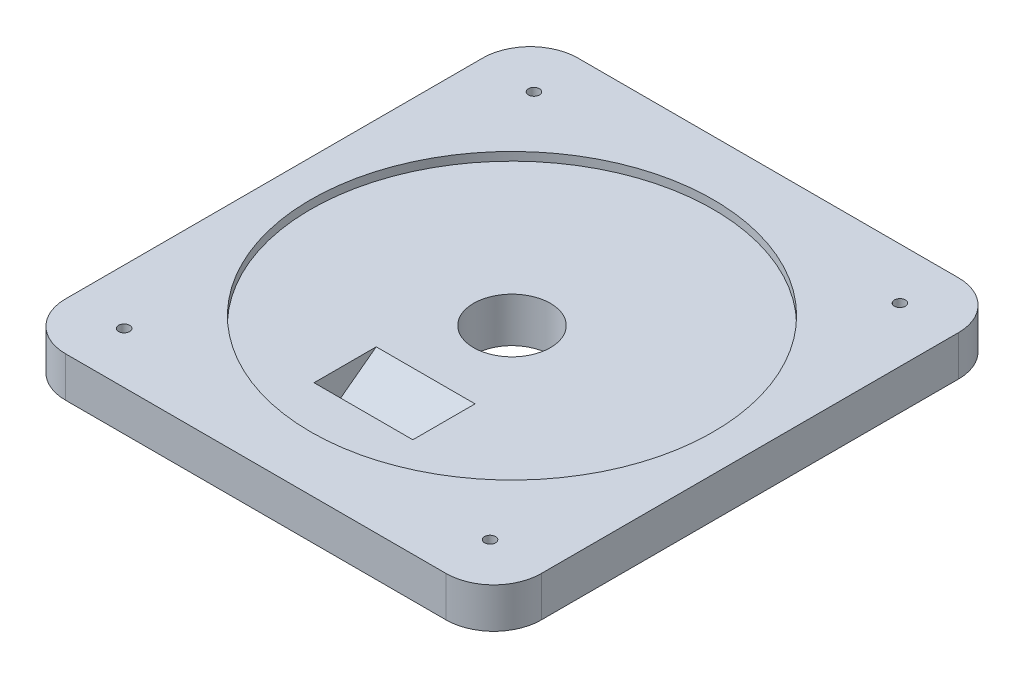
SolidWorks part; units mm, degrees
material "1060 Alloy"
ref_plane "Front Plane" through (0, 0, 0) normal (0, 0, 1) x (1, 0, 0)
ref_plane "Top Plane" through (0, 0, 0) normal (0, 1, 0) x (1, 0, 0)
ref_plane "Right Plane" through (0, 0, 0) normal (1, 0, 0) x (0, 0, -1)
sketch "Sketch2" plane through (0, 0, 0) normal (0, 1, 0) x (1, 0, 0)
  line L1 (-82.55, -88.9) -> (82.55, -88.9)
  line L2 (-82.55, -88.9) -> (-82.55, 88.9)
  line L3 (-82.55, 88.9) -> (82.55, 88.9)
  line L4 (82.55, -88.9) -> (82.55, 88.9)
  point P0 (0, 0)
  point P6 (82.55, 0)
  point P7 (0, 88.9)
  dimension "D1" = 165.1
  dimension "D2" = 177.8
extrude "Boss-Extrude1" add sketch "Sketch2" along normal blind 13.97
fillet "Fillet1" radius 16.51 4 edges at (82.55, 6.985, -88.9) (-82.55, 6.985, -88.9) (-82.55, 6.985, 88.9) (82.55, 6.985, 88.9)
sketch "Sketch3" plane through (0, 0, 0) normal (0, -1, 0) x (1, 0, 0)
  line L0 (-82.55, -72.39) -> (-82.55, 72.39) construction
  line L1 (-66.04, 88.9) -> (66.04, 88.9) construction
  line L2 (66.04, -88.9) -> (-66.04, -88.9) construction
  line L3 (82.55, 72.39) -> (82.55, -72.39) construction
  circle A0 centre (-63.5, 71.12) radius 1.905
  circle A1 centre (63.5, 71.12) radius 1.905
  circle A2 centre (-63.5, -71.12) radius 1.905
  circle A3 centre (63.5, -71.12) radius 1.905
  dimension "D5" = 3.81
  dimension "D1" = 19.05
  dimension "D2" = 17.78
  dimension "D3" = 17.78
  dimension "D4" = 19.05
extrude "Cut-Extrude1" cut sketch "Sketch3" against normal through all
sketch "Sketch5" plane through (0, 0, 0) normal (0, -1, 0) x (1, 0, 0)
  line L0 (-49.2524, 49.53) -> (49.2524, 49.53)
  arc A0 (-49.2524, 49.53) -> (49.2524, 49.53) centre (0, 0) ccw
  dimension "D1" = 139.7
  dimension "D2" = 49.53
extrude "Boss-Extrude2" add sketch "Sketch5" along normal blind 4.445
sketch "Sketch4" plane through (0, 0, 0) normal (0, -1, 0) x (1, 0, 0)
  circle A1 centre (0, 0) radius 13.335
  dimension "D2" = 26.67
extrude "Cut-Extrude3" cut sketch "Sketch4" against normal through all both and the other way through all contours A1
sketch "Sketch7" plane through (0, 0, 0) normal (0, -1, 0) x (1, 0, 0)
  line L0 (-17.145, 51.562) -> (17.145, 51.562)
  line L2 (-66.04, 88.9) -> (66.04, 88.9) construction
  line L6 (82.55, -72.39) -> (82.55, 72.39)
  line L7 (-66.04, -88.9) -> (66.04, -88.9)
  line L8 (-82.55, 72.39) -> (-82.55, -72.39)
  line L9 (66.04, 88.9) -> (-66.04, 88.9)
  line L10 (82.55, -72.39) -> (82.55, 72.39)
  line L11 (-66.04, -88.9) -> (66.04, -88.9)
  line L12 (-82.55, 72.39) -> (-82.55, -72.39)
  line L13 (66.04, 88.9) -> (-66.04, 88.9)
  arc A4 (66.04, -88.9) -> (82.55, -72.39) centre (66.04, -72.39) ccw
  arc A5 (-82.55, -72.39) -> (-66.04, -88.9) centre (-66.04, -72.39) ccw
  arc A6 (-66.04, 88.9) -> (-82.55, 72.39) centre (-66.04, 72.39) ccw
  arc A7 (82.55, 72.39) -> (66.04, 88.9) centre (66.04, 72.39) ccw
  arc A8 (66.04, -88.9) -> (82.55, -72.39) centre (66.04, -72.39) ccw
  arc A9 (-82.55, -72.39) -> (-66.04, -88.9) centre (-66.04, -72.39) ccw
  arc A10 (-66.04, 88.9) -> (-82.55, 72.39) centre (-66.04, 72.39) ccw
  arc A11 (82.55, 72.39) -> (66.04, 88.9) centre (66.04, 72.39) ccw
  point P2 (0, 51.562)
  dimension "D1" = 37.338
  dimension "D2" = 34.29
  dimension "D3" = 0
sketch "Sketch9" plane through (0, 13.97, 0) normal (0, 1, 0) x (1, 0, 0)
  circle A0 centre (0, 0) radius 69.85
  dimension "D1" = 139.7
extrude "Cut-Extrude4" cut sketch "Sketch9" against normal blind 2.921
sketch "Sketch12" plane through (0, 11.049, 0) normal (0, 1, 0) x (1, 0, 0)
  line L0 (17.145, -51.562) -> (-17.145, -51.562)
  line L1 (-66.04, -88.9) -> (66.04, -88.9) construction
  line L2 (17.145, -51.562) -> (17.145, -29.972)
  line L3 (17.145, -29.972) -> (-17.145, -29.972)
  line L4 (-17.145, -29.972) -> (-17.145, -51.562)
  point P2 (0, -51.562)
  dimension "D3" = 29.972
  dimension "D1" = 34.29
  dimension "D2" = 37.338
ref_plane "Plane2" through (0, 0, 51.562) normal (0, 0, -1) x (-1, 0, 0)
sketch "Sketch15" plane through (0, 0, 0) normal (1, 0, 0) x (0, 0, -1)
  line L0 (-51.562, 11.049) -> (-51.562, -5.08)
  line L1 (-51.562, -5.08) -> (-29.972, 11.049)
  line L2 (-29.972, 11.049) -> (-51.562, 11.049)
  dimension "D1" = 16.129
extrude "Cut-Extrude5" cut sketch "Sketch15" against normal mid plane 34.29
